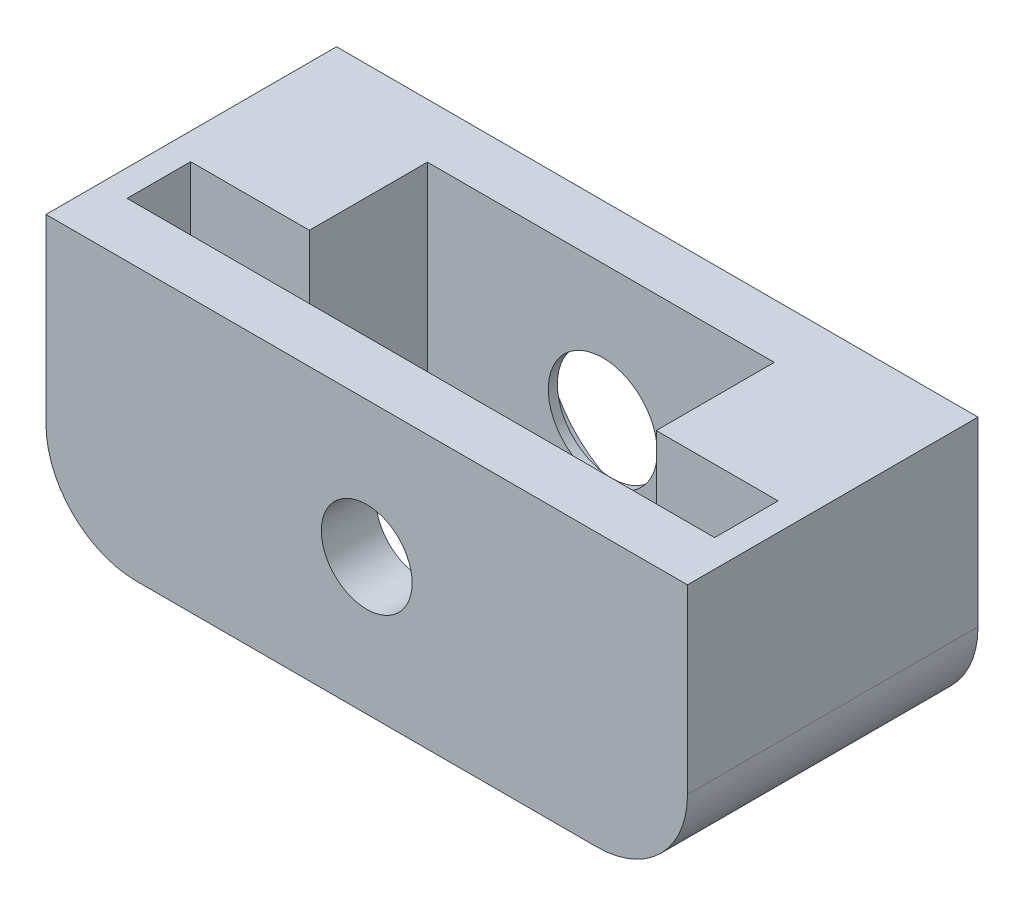
SolidWorks part; units mm, degrees
ref_plane "Front Plane" through (0, 0, 0) normal (0, 0, 1) x (1, 0, 0)
ref_plane "Top Plane" through (0, 0, 0) normal (0, 1, 0) x (1, 0, 0)
ref_plane "Right Plane" through (0, 0, 0) normal (1, 0, 0) x (0, 0, -1)
sketch "Sketch1" plane through (0, 0, 0) normal (0, 0, 1) x (1, 0, 0)
  line L1 (-35.3299, 15) -> (35.3299, 15)
  line L2 (-35.3299, 15) -> (-35.3299, -15)
  line L3 (-35.3299, -15) -> (35.3299, -15)
  line L4 (35.3299, 15) -> (35.3299, -15)
  line L5 (-35.3299, 15) -> (35.3299, -15) construction
  line L6 (-35.3299, -15) -> (35.3299, 15) construction
  point P0 (0, 0)
  dimension "D1" = 30
extrude "Boss-Extrude1" add sketch "Sketch1" along normal blind 6
sketch "Sketch2" plane through (0, 0, 0) normal (0, 0, -1) x (-1, 0, 0)
  circle A0 centre (0, 0) radius 5
extrude "Cut-Extrude1" cut sketch "Sketch2" against normal blind 10
fillet "Fillet1" radius 10 2 edges at (35.3299, -15, 3) (-35.3299, -15, 3)
sketch "Sketch4" plane through (0, 0, 0) normal (0, 0, -1) x (-1, 0, 0)
  line L0 (35.3299, 15) -> (35.3299, -5) construction
  line L1 (-35.3299, -5) -> (-35.3299, 15) construction
  line L2 (35.3299, 15) -> (35.3299, -5)
  line L3 (-35.3299, -5) -> (-35.3299, 15)
  line L4 (-32.317, 15) -> (-32.401, -12.0711)
  line L5 (-35.3299, 15) -> (35.3299, 15) construction
  line L6 (35.3299, 15) -> (32.401, 15)
  line L7 (32.401, 15) -> (32.401, -12.0711)
  arc A0 (25.3299, -15) -> (35.3299, -5) centre (25.3299, -5) ccw construction
  arc A1 (-35.3299, -5) -> (-25.3299, -15) centre (-25.3299, -5) ccw construction
  arc A2 (32.401, -12.0711) -> (35.3299, -5) centre (25.3299, -5) ccw
  arc A3 (-35.3299, -5) -> (-32.401, -12.0711) centre (-25.3299, -5) ccw
  line M2 (-35.3299, 15) -> (-35.3299, -5)
  arc M3 (-35.3299, -5) -> (-25.3299, -15) centre (-25.3299, -5) ccw
  arc M5 (25.3299, -15) -> (35.3299, -5) centre (25.3299, -5) ccw
  line M6 (35.3299, -5) -> (35.3299, 15)
  line M7 (35.3299, 15) -> (-35.3299, 15)
extrude "Boss-Extrude2" add sketch "Sketch4" along normal blind 7 contours L4 M7 M2 M3 | L7 M7 M5 M6
sketch "Sketch6" plane through (0, 0, -7) normal (0, 0, -1) x (-1, 0, 0)
  line L0 (-18.8894, 15) -> (-18.8894, -15)
  line L1 (19.3178, 15) -> (19.3178, -15)
  line L2 (-18.8894, 15) -> (-35.3299, 15)
  line L3 (19.3178, -15) -> (25.3299, -15)
  line L4 (-25.3299, -15) -> (25.3299, -15)
  line L5 (-35.3299, 15) -> (-35.3299, -5)
  line L6 (35.3299, 15) -> (-35.3299, 15)
  line L7 (35.3299, -5) -> (35.3299, 15)
  line L8 (-25.3299, -15) -> (-18.8894, -15)
  line L9 (-35.3299, 15) -> (-35.3299, -5)
  line L10 (35.3299, 15) -> (19.3178, 15)
  line L11 (35.3299, -5) -> (35.3299, 15)
  arc A2 (-35.3299, -5) -> (-25.3299, -15) centre (-25.3299, -5) ccw
  arc A3 (25.3299, -15) -> (35.3299, -5) centre (25.3299, -5) ccw
  arc A4 (-35.3299, -5) -> (-25.3299, -15) centre (-25.3299, -5) ccw
  arc A5 (25.3299, -15) -> (35.3299, -5) centre (25.3299, -5) ccw
  dimension "D1" = 0
extrude "Boss-Extrude3" add sketch "Sketch6" along normal blind 13
fillet "Fillet2" radius 6 2 edges at (-19.3178, -15, -13.5) (18.8894, -15, -13.5)
sketch "Sketch7" plane through (0, 0, -20) normal (0, 0, -1) x (-1, 0, 0)
  line L4 (-25.3299, -15) -> (25.3299, -15)
  line L5 (-35.3299, 15) -> (-35.3299, -5)
  line L6 (35.3299, 15) -> (-35.3299, 15)
  line L7 (35.3299, -5) -> (35.3299, 15)
  line L8 (-25.3299, -15) -> (25.3299, -15)
  line L9 (-35.3299, 15) -> (-35.3299, -5)
  line L10 (35.3299, 15) -> (-35.3299, 15)
  line L11 (35.3299, -5) -> (35.3299, 15)
  arc A2 (-35.3299, -5) -> (-25.3299, -15) centre (-25.3299, -5) ccw
  arc A3 (25.3299, -15) -> (35.3299, -5) centre (25.3299, -5) ccw
  arc A4 (-35.3299, -5) -> (-25.3299, -15) centre (-25.3299, -5) ccw
  arc A5 (25.3299, -15) -> (35.3299, -5) centre (25.3299, -5) ccw
  dimension "D1" = 0
extrude "Boss-Extrude4" add sketch "Sketch7" along normal blind 6
sketch "Sketch8" plane through (0, 0, -20) normal (0, 0, 1) x (1, 0, 0)
  circle A0 centre (0, 0) radius 6
  dimension "D1" = 12
extrude "Cut-Extrude2" cut sketch "Sketch8" against normal blind 30
sketch "Sketch9" plane through (0, 0, -26) normal (0, 0, -1) x (-1, 0, 0)
  circle A0 centre (0, 0) radius 12.5
  dimension "D1" = 25
extrude "Cut-Extrude3" cut sketch "Sketch9" against normal blind 5
